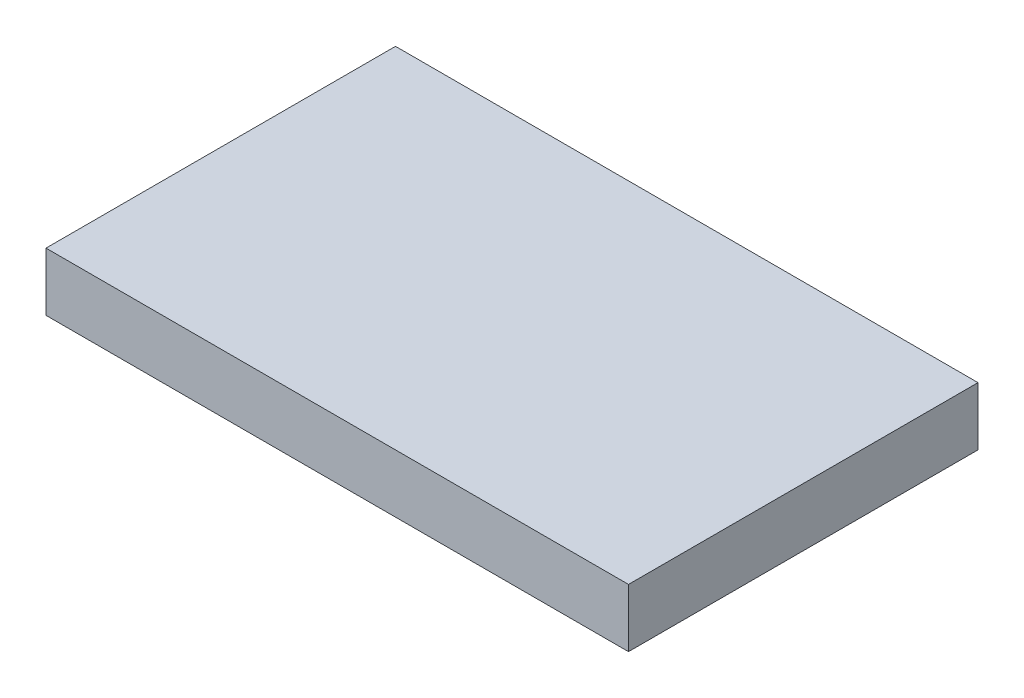
SolidWorks part; units mm, degrees
ref_plane "Front Plane" through (0, 0, 0) normal (0, 0, 1) x (1, 0, 0)
ref_plane "Top Plane" through (0, 0, 0) normal (0, 1, 0) x (1, 0, 0)
ref_plane "Right Plane" through (0, 0, 0) normal (1, 0, 0) x (0, 0, -1)
sketch "Sketch1" plane through (0, 0, 0) normal (0, 1, 0) x (1, 0, 0)
  line L1 (-34.1923, 24.2174) -> (29.3077, 24.2174)
  line L2 (-34.1923, 24.2174) -> (-34.1923, -13.8826)
  line L3 (-34.1923, -13.8826) -> (29.3077, -13.8826)
  line L4 (29.3077, 24.2174) -> (29.3077, -13.8826)
  dimension "D1" = 63.5
  dimension "D2" = 38.1
extrude "Boss-Extrude1" add sketch "Sketch1" along normal blind 6.35
